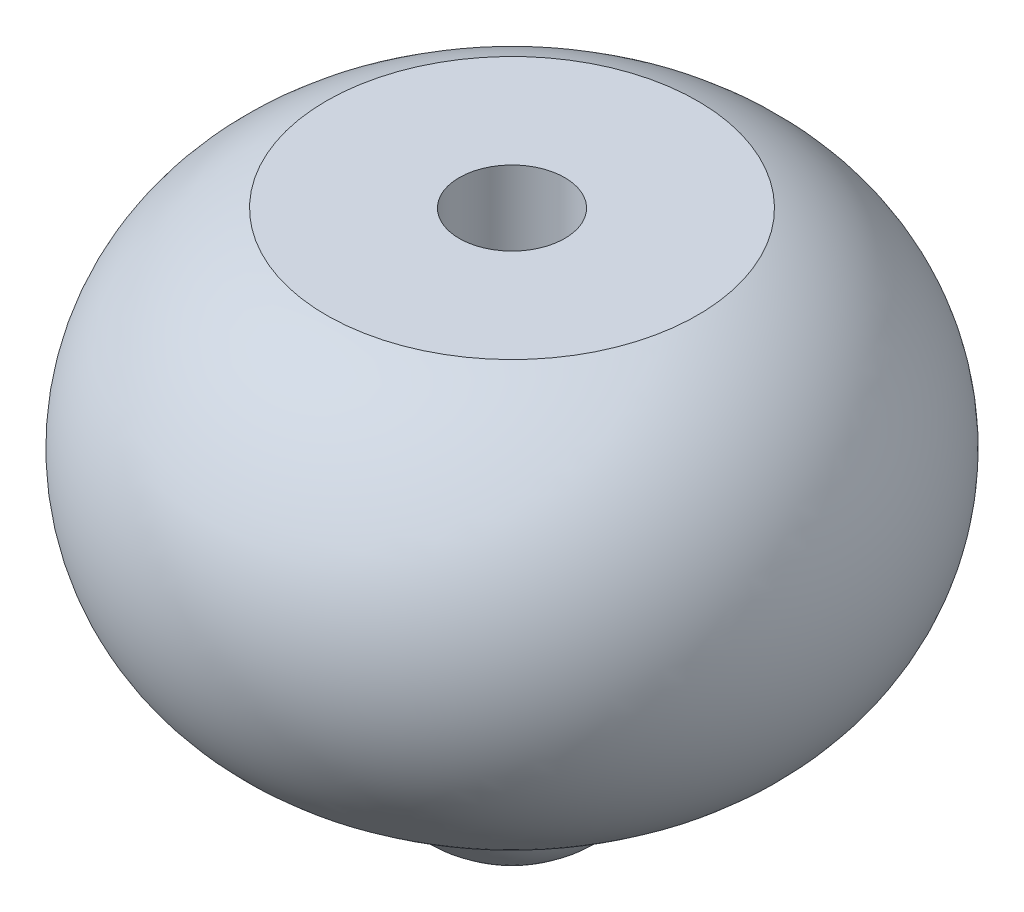
SolidWorks part; units mm, degrees
ref_plane "Front Plane" through (0, 0, 0) normal (0, 0, 1) x (1, 0, 0)
ref_plane "Top Plane" through (0, 0, 0) normal (0, 1, 0) x (1, 0, 0)
ref_plane "Right Plane" through (0, 0, 0) normal (1, 0, 0) x (0, 0, -1)
sketch "Sketch1" plane through (0, 0, 0) normal (0, 0, 1) x (1, 0, 0)
  line L0 (67.1666, 0.2652) -> (67.1662, 49.2475)
  line L1 (67.1662, 49.2475) -> (50.4142, 49.2475)
  arc A0 (50.4142, 49.2475) -> (56.4282, 10.446) centre (57.4709, 30.4744) ccw
  arc A1 (67.1666, 0.2652) -> (56.4282, 10.446) centre (67.1665, 11.0187) cw
  point P6 (0, 0)
revolve "Revolve1" add sketch "Sketch1" angle 360 about L0
ref_plane "Plane1" through (-0.0004, 49.2471, 0) normal (0, -1, 0) x (-1, 0, 0)
sketch "Sketch2" plane through (-0.0004, 49.2471, 0) normal (0, -1, 0) x (-1, 0, 0)
  circle A0 centre (-67.1666, 0) radius 4.7625
  dimension "D1" = 9.525
extrude "Cut-Extrude1" cut sketch "Sketch2" against normal blind 2.54 and the other way blind 25.4
